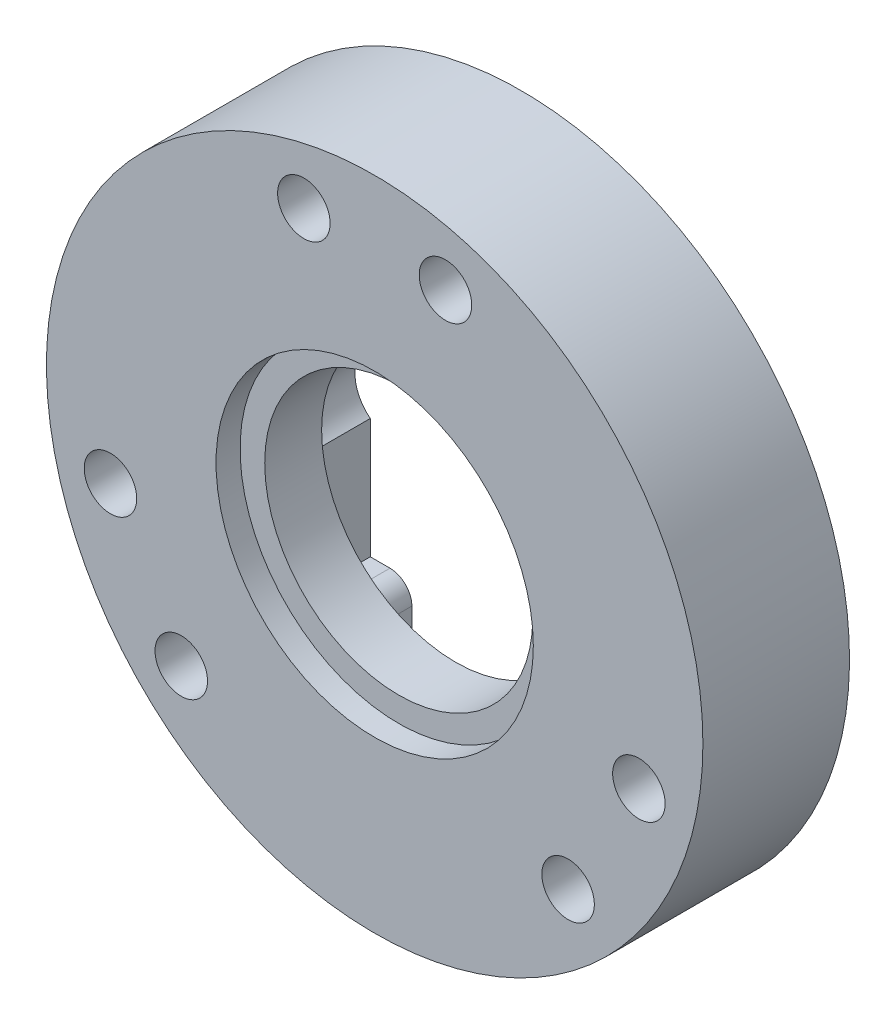
SolidWorks part; units mm, degrees
ref_plane "정면" through (0, 0, 0) normal (0, 0, 1) x (1, 0, 0)
ref_plane "윗면" through (0, 0, 0) normal (0, 1, 0) x (1, 0, 0)
ref_plane "우측면" through (0, 0, 0) normal (1, 0, 0) x (0, 0, -1)
sketch "스케치1" plane through (0, 0, 0) normal (0, 0, 1) x (1, 0, 0)
  line L0 (-5, -6.9) -> (-6.9, -6.9)
  line L2 (-5, -6.9) -> (-5, -14.1421)
  line L3 (0, -6.9) -> (0, -15) construction
  line L4 (5, -6.9) -> (5, -14.1421)
  line L6 (6.9, -6.9) -> (5, -6.9)
  line L7 (6.9, -6.9) -> (6.9, 6.9)
  line L8 (6.9, 6.9) -> (-6.9, 6.9)
  line L9 (-6.9, -6.9) -> (-6.9, 6.9)
  arc A0 (5, -14.1421) -> (-5, -14.1421) centre (0, 0) ccw
  circle A2 centre (0, 9.5) radius 2.1 construction
  circle A3 centre (0, 0) radius 9.5 construction
  point P1 (0, 6.9)
  point P15 (6.9, 0)
  point P19 (0, 0)
  point P28 (0, 0)
  dimension "D1" = 30
  dimension "D2" = 4.2
  dimension "D6" = 13.8
  dimension "D7" = 5
  dimension "D8" = 13.8
  dimension "D3" = 19
extrude "보스-돌출1" add sketch "스케치1" along normal blind 3
sketch "스케치11" plane through (0, 0, 3) normal (0, 0, 1) x (1, 0, 0)
  line L0 (5.8, 0) -> (-5.8, 0) construction
  line L1 (5.8, 0) -> (-5.8, 0) construction
  line L2 (5.8, -1.8) -> (-5.8, -1.8)
  line L3 (5.8, 1.8) -> (-5.8, 1.8)
  arc A0 (5.8, -1.8) -> (5.8, 1.8) centre (5.8, 0) ccw
  arc A1 (-5.8, 1.8) -> (-5.8, -1.8) centre (-5.8, 0) ccw
  point P4 (0, 0)
  point P6 (0, 0)
  dimension "D2" = 1.8
  dimension "D1" = 11.6
extrude "컷-돌출4" cut sketch "스케치11" against normal through all
sketch "스케치12" plane through (0, 0, 3) normal (0, 0, 1) x (1, 0, 0)
  circle A0 centre (0, 0) radius 15
  circle A1 centre (0, 0) radius 6.125
  dimension "D1" = 30
  dimension "D2" = 12.25
extrude "보스-돌출2" add sketch "스케치12" along normal blind 2.6
sketch "스케치13" plane through (0, 0, 5.6) normal (0, 0, 1) x (1, 0, 0)
  circle A0 centre (0, 0) radius 7.25
  circle A1 centre (0, 0) radius 15
  dimension "D1" = 14.5
  dimension "D2" = 30
extrude "보스-돌출3" add sketch "스케치13" along normal blind 1.1
sketch "스케치14" plane through (0, 0, 6.7) normal (0, 0, 1) x (1, 0, 0)
  line L0 (0, 0) -> (-3.2352, 12.0741) construction
  line L1 (0, 0) -> (0, 15) construction
  line L2 (0, 0) -> (3.2352, 12.0741) construction
  circle A0 centre (0, 0) radius 15 construction
  circle A1 centre (3.2352, 12.0741) radius 1.2
  circle A2 centre (-3.2352, 12.0741) radius 1.2
  circle A3 centre (12.0741, -3.2352) radius 1.2
  circle A4 centre (8.8388, -8.8388) radius 1.2
  circle A5 centre (-8.8388, -8.8388) radius 1.2
  circle A6 centre (-12.0741, -3.2352) radius 1.2
  point P17 (0, 0)
  dimension "D1" = 2.4
  dimension "D3" = 30
  dimension "D2" = 12.5
  dimension "D5" = 12.5
  dimension "D6" = 15
  dimension "D4" = 3
extrude "컷-돌출5" cut sketch "스케치14" against normal through all
fillet "필렛1" radius 1 2 edges at (-5, -6.9, 1.5) (5, -6.9, 1.5)
